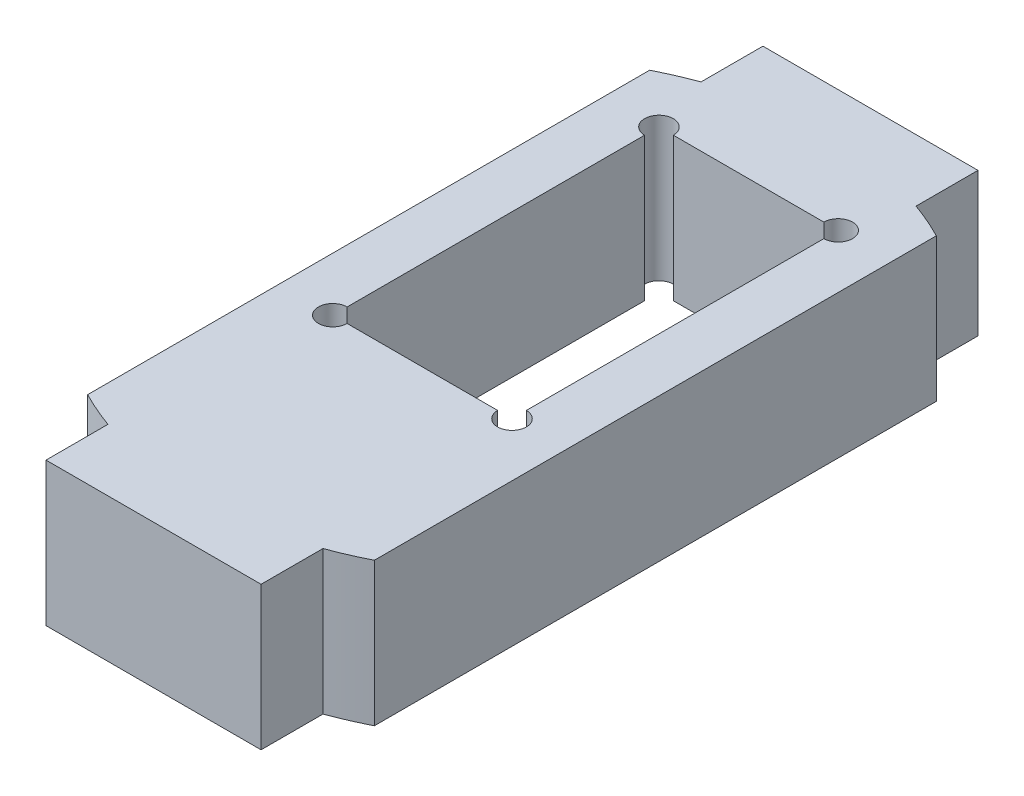
SolidWorks part; units mm, degrees
material "PE Alta Densidade"
ref_plane "Front" through (0, 0, 0) normal (0, 0, 1) x (1, 0, 0)
ref_plane "Top" through (0, 0, 0) normal (0, 1, 0) x (1, 0, 0)
ref_plane "Right" through (0, 0, 0) normal (1, 0, 0) x (0, 0, -1)
sketch "Esboço1" plane through (0, 0, 0) normal (0, 1, 0) x (1, 0, 0)
  line L0 (-7.5, 20.6821) -> (-7.5, 25)
  line L1 (-7.5, -25) -> (7.5, -25)
  line L2 (-7.5, -25) -> (-7.5, -20.6821)
  line L3 (-7.5, 25) -> (7.5, 25)
  line L4 (7.5, -25) -> (7.5, -20.6821)
  line L5 (0, 94.3548) -> (0, -102.4194) construction
  line L6 (7.5, 20.6821) -> (7.5, 25)
  line L7 (-104.5161, 0) -> (103.2258, 0) construction
  line L8 (-10, -19.5959) -> (-10, 19.5959)
  line L9 (10, -19.5959) -> (10, 19.5959)
  arc A0 (-7.5, 20.6821) -> (-10, 19.5959) centre (0, 0) ccw
  arc A1 (7.5, -20.6821) -> (10, -19.5959) centre (0, 0) ccw
  arc A2 (-7.5, 20.6821) -> (-7.5, -20.6821) centre (0, 0) ccw construction
  arc A3 (7.5, 23.8485) -> (-7.5, 23.8485) centre (0, 0) ccw construction
  arc A4 (-10, -19.5959) -> (-7.5, -20.6821) centre (0, 0) ccw
  arc A5 (10, 19.5959) -> (7.5, 20.6821) centre (0, 0) ccw
  dimension "D1" = 15
  dimension "D2" = 10
extrude "Ressalto-extrusão1" add sketch "Esboço1" along normal blind 10
sketch "Esboço2" plane through (0, 10, 0) normal (0, 1, 0) x (1, 0, 0)
  line L0 (-6.25, -5.95) -> (-6.25, 16.2) construction
  line L2 (5.25, 16.5) -> (-5.25, 16.5)
  line L3 (6.25, 15.5) -> (6.25, -5.25)
  line L4 (5.25, -6.25) -> (-5.25, -6.25)
  line L5 (-6.25, 15.5) -> (-6.25, -5.25)
  line L6 (-5.95, 16.5) -> (5.95, 16.5) construction
  line L7 (6.25, 16.2) -> (6.25, -5.95) construction
  line L8 (5.95, -6.25) -> (-5.95, -6.25) construction
  line L9 (-6.25, -6.25) -> (6.25, -6.25) construction
  line L10 (-6.25, -6.25) -> (-6.25, 16.5) construction
  line L11 (-6.25, 16.5) -> (6.25, 16.5) construction
  line L12 (6.25, -6.25) -> (6.25, 16.5) construction
  arc A0 (-6.25, -5.25) -> (-5.25, -6.25) centre (-6.25, -6.25) ccw
  arc A1 (-5.25, 16.5) -> (-6.25, 15.5) centre (-6.25, 16.5) ccw
  arc A2 (6.25, 15.5) -> (5.25, 16.5) centre (6.25, 16.5) ccw
  arc A3 (5.25, -6.25) -> (6.25, -5.25) centre (6.25, -6.25) ccw
  dimension "D1" = 2
extrude "Corte-extrusão1" cut sketch "Esboço2" against normal through all
